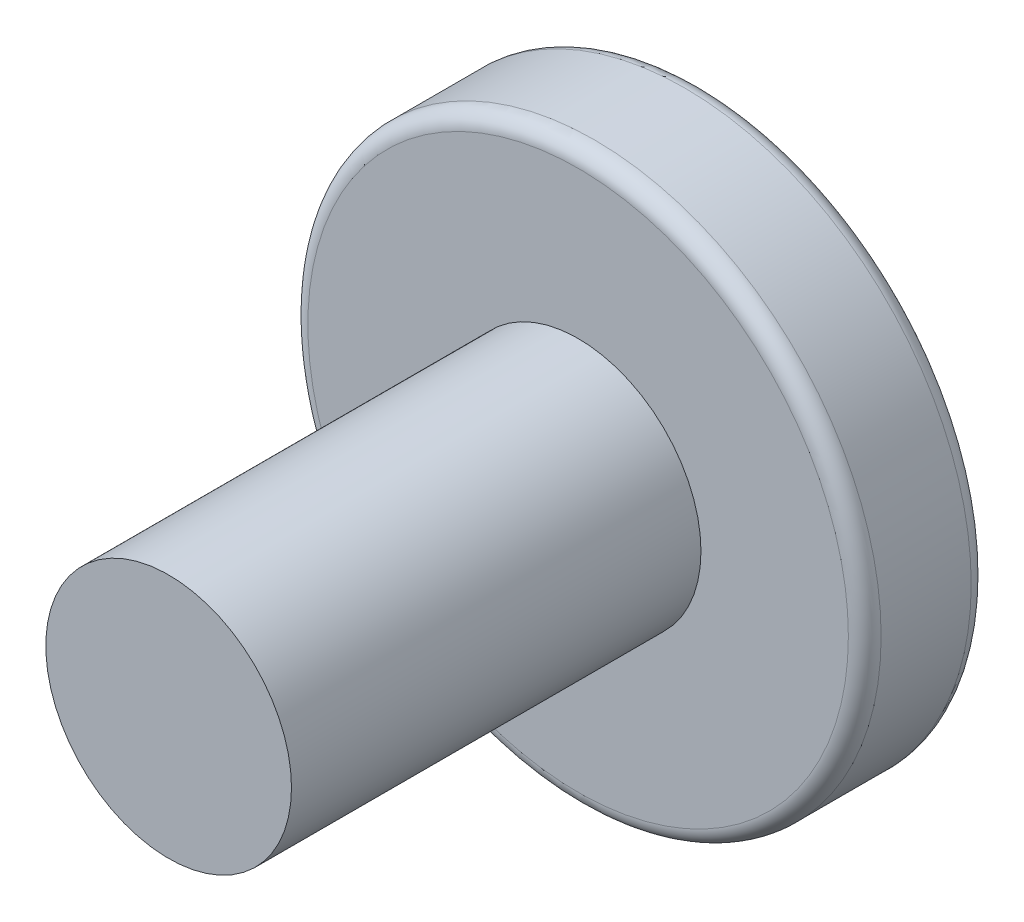
SolidWorks part; units mm, degrees
material "AISI 304"
ref_plane "前视基准面" through (0, 0, 0) normal (0, 0, 1) x (1, 0, 0)
ref_plane "上视基准面" through (0, 0, 0) normal (0, 1, 0) x (1, 0, 0)
ref_plane "右视基准面" through (0, 0, 0) normal (1, 0, 0) x (0, 0, -1)
other "Configuration Table"
sketch "草图1" plane through (0, 0, 0) normal (0, 0, 1) x (1, 0, 0)
  circle A0 centre (0, 0) radius 3.5
  dimension "D1" = 7
extrude "凸台-拉伸1" add sketch "草图1" along normal blind 1.5
sketch "草图2" plane through (0, 0, 1.5) normal (0, 0, 1) x (1, 0, 0)
  circle A1 centre (0, 0) radius 1.5
  dimension "D2" = 3
extrude "凸台-拉伸2" add sketch "草图2" along normal blind 5
fillet "圆角1" radius 0.2 2 edges at (3.5, 0, 0) (3.5, 0, 1.5)
sketch "草图3" plane through (0, 0, 0) normal (0, 0, -1) x (-1, 0, 0)
  line L0 (0, 0) -> (1.1547, 0) construction
  line L1 (1.1547, 0) -> (0.5774, 1)
  line L2 (0.5774, 1) -> (-0.5774, 1)
  line L3 (-0.5774, 1) -> (-1.1547, 0)
  line L4 (-1.1547, 0) -> (-0.5774, -1)
  line L5 (-0.5774, -1) -> (0.5774, -1)
  line L6 (0.5774, -1) -> (1.1547, 0)
  circle A0 centre (0, 0) radius 1 construction
  dimension "D1" = 2
extrude "切除-拉伸1" cut sketch "草图3" against normal blind 1.5
